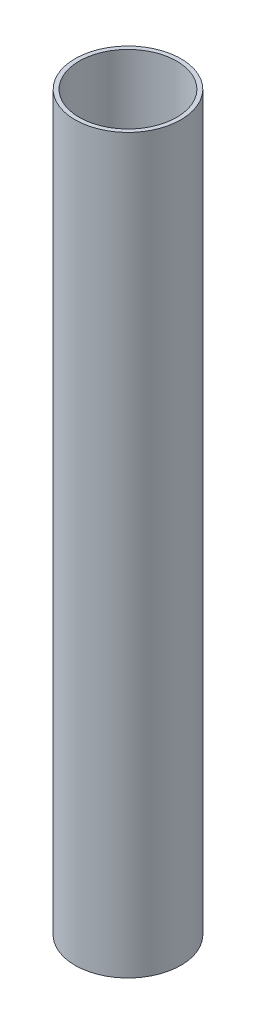
SolidWorks part; units mm, degrees
ref_plane "Front Plane" through (0, 0, 0) normal (0, 0, 1) x (1, 0, 0)
ref_plane "Top Plane" through (0, 0, 0) normal (0, 1, 0) x (1, 0, 0)
ref_plane "Right Plane" through (0, 0, 0) normal (1, 0, 0) x (0, 0, -1)
sketch "Sketch1" plane through (0, 0, 0) normal (0, 1, 0) x (1, 0, 0)
  circle A0 centre (0, 0) radius 15.9
  circle A1 centre (0, 0) radius 14.65
  dimension "D1" = 31.8
  dimension "D2" = 29.3
extrude "Boss-Extrude1" add sketch "Sketch1" along normal blind 220
